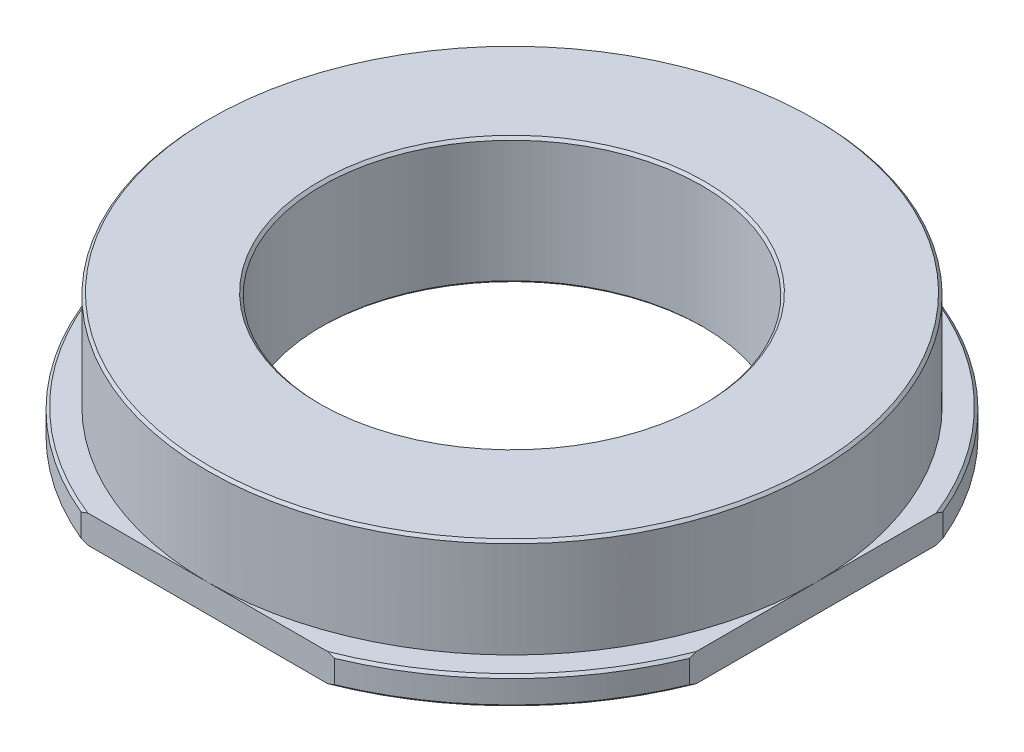
SolidWorks part; units mm, degrees
ref_plane "Front Plane" through (0, 0, 0) normal (0, 0, 1) x (1, 0, 0)
ref_plane "Top Plane" through (0, 0, 0) normal (0, 1, 0) x (1, 0, 0)
ref_plane "Right Plane" through (0, 0, 0) normal (1, 0, 0) x (0, 0, -1)
other "Configuration Table"
sketch "草图1" plane through (0, 0, 0) normal (0, 1, 0) x (1, 0, 0)
  circle A0 centre (0, 0) radius 13
extrude "凸台-拉伸1" add sketch "草图1" along normal blind 1.1
sketch "草图2" plane through (0, 1.1, 0) normal (0, 1, 0) x (1, 0, 0)
  circle A0 centre (0, 0) radius 12
extrude "凸台-拉伸2" add sketch "草图2" along normal blind 3.9
sketch "草图3" plane through (0, 5, 0) normal (0, 1, 0) x (1, 0, 0)
  circle A0 centre (0, 0) radius 7.5
extrude "切除-拉伸1" cut sketch "草图3" against normal through all
chamfer "倒角1" distance 0.1 angle 45 5 edges at (0, 0, 7.5) (0, 5, 7.5) (0, 5, 12) (0, 0, 13) (0, 1.1, 13)
sketch "草图7" plane through (0, 1.1, 0) normal (0, 1, 0) x (1, 0, 0)
  line L1 (-5, 12) -> (5, 12)
  line L2 (-12, 5) -> (-12, -5)
  line L3 (-5, -12) -> (5, -12)
  line L4 (12, 5) -> (12, -5)
  arc A0 (-12, 5) -> (-12, -5) centre (0, 0) ccw
  arc A1 (5, 12) -> (-5, 12) centre (0, 0) ccw
  arc A2 (12, -5) -> (12, 5) centre (0, 0) ccw
  arc A3 (-5, -12) -> (5, -12) centre (0, 0) ccw
  point P0 (0, 0)
extrude "切除-拉伸2" cut sketch "草图7" against normal through all
